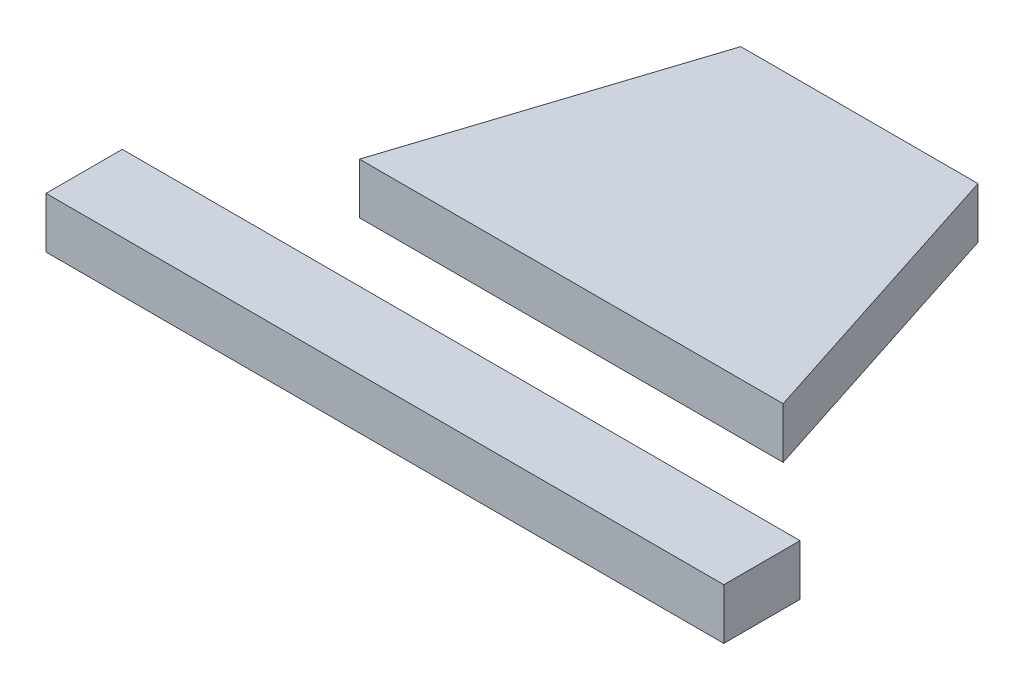
SolidWorks part; units mm, degrees
ref_plane "Front Plane" through (0, 0, 0) normal (0, 0, 1) x (1, 0, 0)
ref_plane "Top Plane" through (0, 0, 0) normal (0, 1, 0) x (1, 0, 0)
ref_plane "Right Plane" through (0, 0, 0) normal (1, 0, 0) x (0, 0, -1)
sketch "Sketch1" plane through (0, 0, 0) normal (0, 1, 0) x (1, 0, 0)
  line L0 (0, -2.5) -> (0, 26.5234) construction
  line L1 (-20, 2.25) -> (20, 2.25)
  line L2 (-20, 2.25) -> (-20, -2.25)
  line L3 (-20, -2.25) -> (20, -2.25)
  line L4 (20, 2.25) -> (20, -2.25)
  line L5 (-20, 2.25) -> (20, -2.25) construction
  line L6 (-20, -2.25) -> (20, 2.25) construction
  line L7 (-12.5, 8.75) -> (12.5, 8.75)
  line L8 (-7, 25.75) -> (7, 25.75)
  line L9 (-7, 25.75) -> (-12.5, 8.75)
  line L10 (7, 25.75) -> (12.5, 8.75)
  point P0 (0, 0)
  point P11 (0, 8.75)
  point P14 (0, 25.75)
  dimension "D1" = 4.5
  dimension "D2" = 40
  dimension "D3" = 6.5
  dimension "D4" = 25
  dimension "D5" = 17
  dimension "D6" = 14
extrude "Boss-Extrude1" add sketch "Sketch1" along normal blind 3 contours L4 L1 L2 L3 | L10 L7 L9 L8
